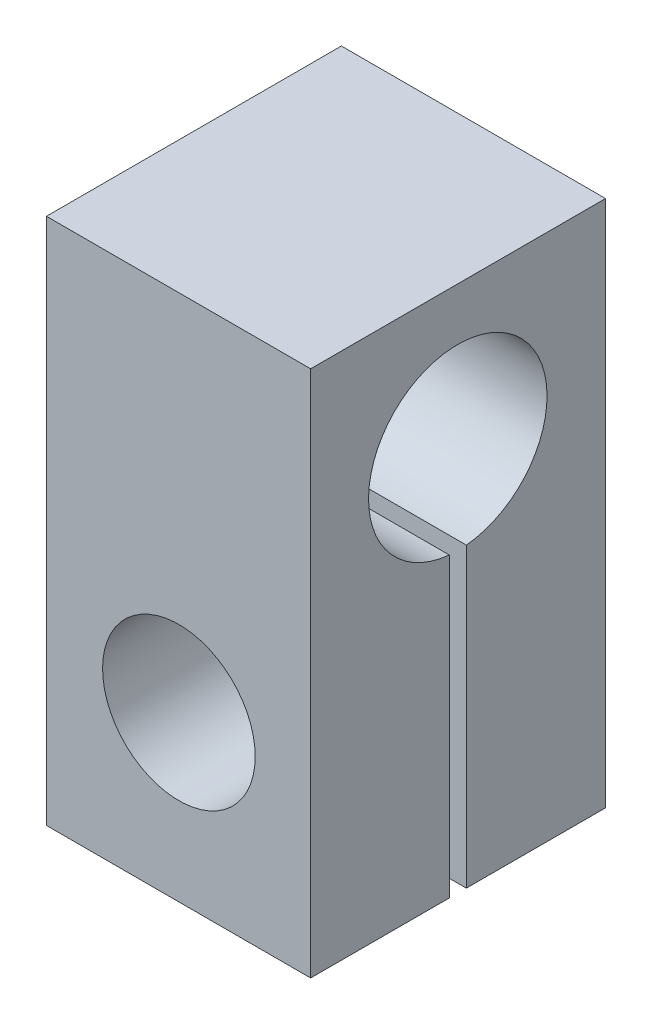
SolidWorks part; units mm, degrees
ref_plane "Front Plane" through (0, 0, 0) normal (0, 0, 1) x (1, 0, 0)
ref_plane "Top Plane" through (0, 0, 0) normal (0, 1, 0) x (1, 0, 0)
ref_plane "Right Plane" through (0, 0, 0) normal (1, 0, 0) x (0, 0, -1)
sketch "Sketch1" plane through (0, 0, 0) normal (1, 0, 0) x (0, 0, -1)
  line L0 (1.5561, -9.9154) -> (3.9177, -9.9163)
  line L1 (1.5561, -0.9285) -> (1.5561, -9.9154)
  line L2 (6.5797, -9.9174) -> (6.5797, -0.9285)
  line L3 (4.2083, -9.9164) -> (6.5797, -9.9174)
  line L8 (1.5561, -0.9285) -> (6.5797, -0.9285)
  line L9 (3.9177, -4.8555) -> (3.9177, -9.9163)
  line L11 (4.2083, -4.8555) -> (4.2083, -9.9164)
  arc A0 (4.2083, -4.8555) -> (3.9177, -4.8555) centre (4.0628, -3.3424) ccw
extrude "Boss-Extrude2" add sketch "Sketch1" along normal blind 4.5
sketch "Sketch3" plane through (0, 0, -1.5561) normal (0, 0, 1) x (1, 0, 0)
  circle A0 centre (2.256, -7.1217) radius 1.3
  circle A1 centre (2.256, -7.1217) radius 1.3
  point P3 (2.25, -6.6083)
  point P4 (2.3357, -7.0282)
  point P5 (0, 0)
  point P6 (2.256, -7.1217)
extrude "Cut-Extrude1" cut sketch "Sketch3" against normal blind 10.5 contours A0
